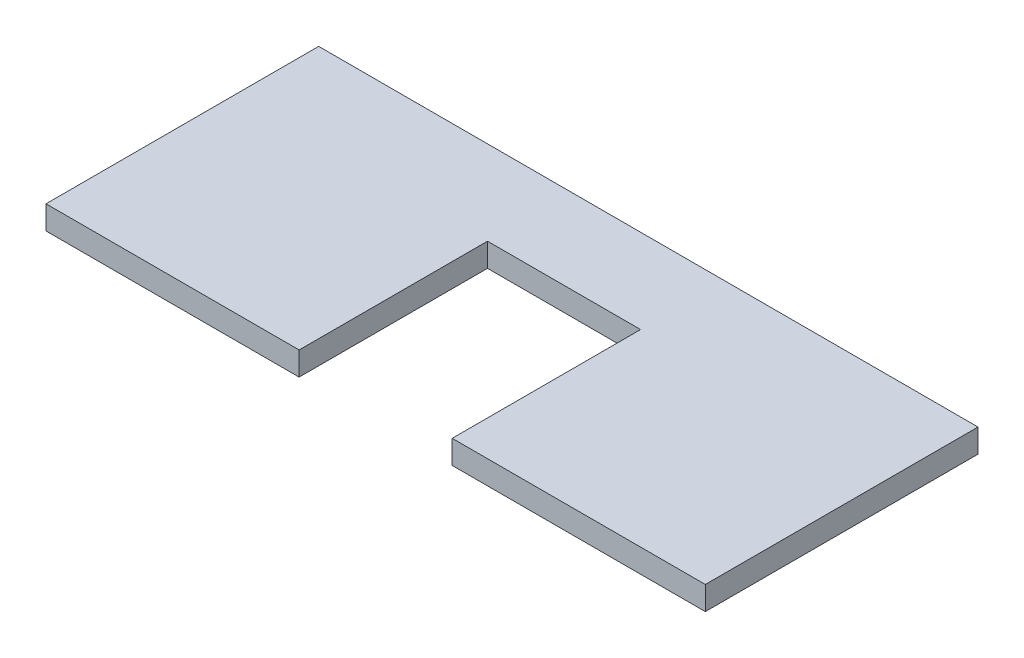
SolidWorks part; units mm, degrees
ref_plane "Front Plane" through (0, 0, 0) normal (0, 0, 1) x (1, 0, 0)
ref_plane "Top Plane" through (0, 0, 0) normal (0, 1, 0) x (1, 0, 0)
ref_plane "Right Plane" through (0, 0, 0) normal (1, 0, 0) x (0, 0, -1)
sketch "Sketch1" plane through (0, 0, 0) normal (0, 1, 0) x (1, 0, 0)
  line L0 (-41.275, -101.6) -> (-41.275, 0)
  line L1 (-177.8, 45.466) -> (177.8, 45.466)
  line L2 (-177.8, 45.466) -> (-177.8, -101.6)
  line L3 (-177.8, -101.6) -> (-41.275, -101.6)
  line L4 (177.8, 45.466) -> (177.8, -101.6)
  line L5 (0, 45.466) -> (0, 0) construction
  line L6 (0, 0) -> (0, 304.3208) construction
  line L7 (41.275, -101.6) -> (41.275, 0)
  line L8 (-41.275, 0) -> (41.275, 0)
  line L9 (41.275, -101.6) -> (177.8, -101.6)
  dimension "D1" = 355.6
  dimension "D2" = 147.066
  dimension "D3" = 82.55
  dimension "4" = 101.6
extrude "Boss-Extrude1" add sketch "Sketch1" along normal blind 12.7
